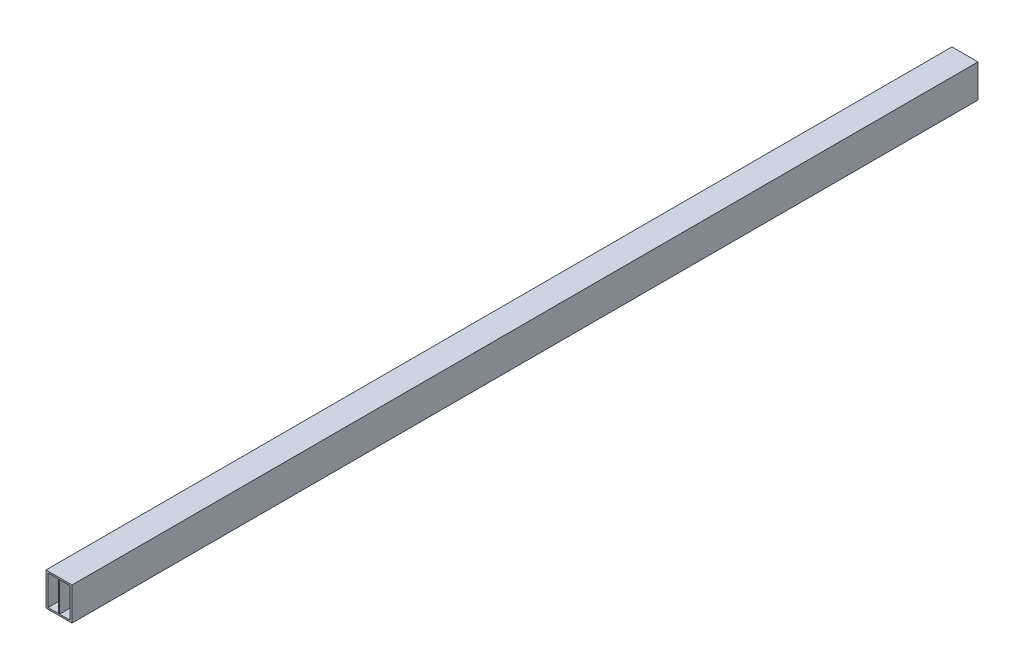
SolidWorks part; units mm, degrees
material "ASTM A992 Steel"
ref_plane "Front" through (0, 0, 0) normal (0, 0, 1) x (1, 0, 0)
ref_plane "Top" through (0, 0, 0) normal (0, 1, 0) x (1, 0, 0)
ref_plane "Right" through (0, 0, 0) normal (1, 0, 0) x (0, 0, -1)
sketch "Sketch1" plane through (0, 0, 0) normal (0, 0, 1) x (1, 0, 0)
  line L0 (0, -0.0002) -> (101.6, -0.0002)
  line L1 (101.6, -0.0002) -> (101.6, -7.1122)
  line L2 (101.6, -7.1122) -> (53.408, -7.1122)
  line L3 (53.408, -7.1122) -> (53.408, -146.0502)
  line L4 (53.408, -146.0502) -> (101.6, -146.0502)
  line L5 (101.6, -146.0502) -> (101.6, -153.1622)
  line L6 (101.6, -153.1622) -> (0, -153.1622)
  line L7 (0, -153.1622) -> (0, -146.0502)
  line L8 (0, -146.0502) -> (47.566, -146.0502)
  line L9 (47.566, -146.0502) -> (47.566, -7.1122)
  line L10 (47.566, -7.1122) -> (0, -7.1122)
  line L11 (0, -7.1122) -> (0, -0.0002)
  line L12 (50.8, -0.0002) -> (50.8, -153.1622) construction
  dimension "D1" = 5.842
  dimension "D2" = 7.112
  dimension "D3" = 7.112
  dimension "D4" = 7.112
  dimension "D5" = 153.162
  dimension "D6" = 50.8
  dimension "D7" = 50.8
  dimension "D8" = 47.566
extrude "Boss-Extrude1" add sketch "Sketch1" along normal blind 4200
sketch "Sketch2" plane through (0, -153.1622, 0) normal (0, -1, 0) x (1, 0, 0)
  line L2 (101.6, 4200) -> (101.6, 0) construction
  line L5 (101.6, 2100) -> (101.6, 2252.4)
  line L6 (101.6, 2252.4) -> (-229.7319, 2252.4)
  line L7 (-229.7319, 2000) -> (-229.7319, 2252.4)
  line L9 (101.6, 2100) -> (101.6, 1947.6)
  line L10 (101.6, 1947.6) -> (-229.7319, 1947.6)
  line L11 (-229.7319, 2000) -> (-229.7319, 1947.6)
  point P0 (101.6, 2100)
  dimension "D1" = 152.4
  dimension "D2" = 152.4
split line "Split Line1"
sketch "Sketch3" plane through (101.6, 0, 0) normal (1, 0, 0) x (0, 0, -1)
  line L1 (-4200, -0.0002) -> (0, -0.0002)
  line L2 (-4200, -0.0002) -> (-4200, -153.1622)
  line L3 (-4200, -153.1622) -> (0, -153.1622)
  line L4 (0, -0.0002) -> (0, -153.1622)
extrude "Boss-Extrude2" add sketch "Sketch3" along normal blind 9.525
sketch "Sketch4" plane through (0, 0, 0) normal (-1, 0, 0) x (0, 0, 1)
  line L1 (0, -153.1622) -> (4200, -153.1622)
  line L2 (0, -153.1622) -> (0, -0.0002)
  line L3 (0, -0.0002) -> (4200, -0.0002)
  line L4 (4200, -153.1622) -> (4200, -0.0002)
extrude "Boss-Extrude3" add sketch "Sketch4" along normal blind 9.525
